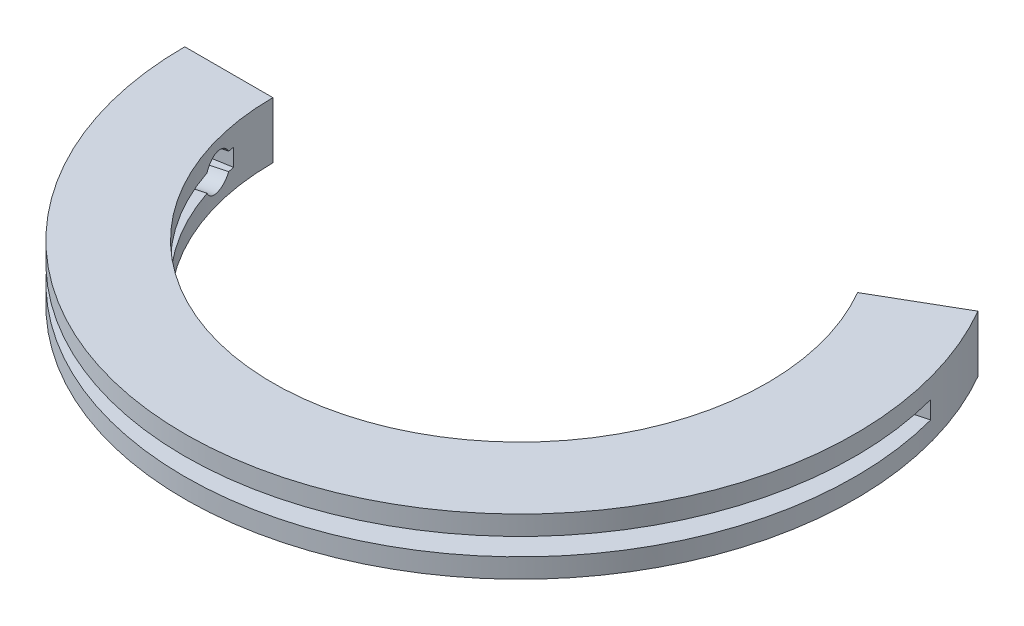
SolidWorks part; units mm, degrees
ref_plane "前视基准面" through (0, 0, 0) normal (0, 0, 1) x (1, 0, 0)
ref_plane "上视基准面" through (0, 0, 0) normal (0, 1, 0) x (1, 0, 0)
ref_plane "右视基准面" through (0, 0, 0) normal (1, 0, 0) x (0, 0, -1)
sketch "草图4" plane through (0, 0, 0) normal (0, 0, 1) x (1, 0, 0)
  line L1 (-949.5262, 0) -> (-949.5262, -80)
  line L2 (-949.5262, -80) -> (-700, -80)
  line L5 (-750, 436.001) -> (-750, -447.2545) construction
  line L6 (-700, 80) -> (-949.5262, 80)
  line L7 (-949.5262, 80) -> (-949.5262, 0)
  line L8 (0, 0) -> (0, 457.5891) construction
  line L9 (0, 50) -> (0, -50) construction
  line L10 (-700, 80) -> (-700, -80)
  line L11 (0, 533.1534) -> (0, -616.7503) construction
  line L12 (0, 0) -> (-1108.9843, 0) construction
  dimension "D1" = 750
  dimension "D2" = 700
  dimension "D3" = 80
  dimension "D4" = 950
  dimension "D5" = 160
revolve "旋转3" add sketch "草图4" angle 210 about L8
sketch "草图7" plane through (0, 0, 0) normal (0, 1, 0) x (1, 0, 0)
  line L0 (0, 0) -> (269.1765, -1004.5805) construction
  line L1 (-700, 0) -> (-949.5262, 0) construction
  line L2 (0, 0) -> (-1229.8518, -329.5378) construction
  dimension "D1" = 105
  dimension "D2" = 90
sketch "草图9" plane through (0, 0, 0) normal (0, 0, 1) x (1, 0, 0)
  line L0 (0, 442.4596) -> (0, -553.6878) construction
ref_plane "基准面5" through (0, 0, 0) normal (0.2588, 0, 0.9659) x (0.9659, 0, -0.2588)
sketch "草图10" plane through (0, 0, 0) normal (0.2588, 0, 0.9659) x (0.9659, 0, -0.2588)
  line L0 (-750, 50) -> (750, 50)
  line L5 (-1326.134, 0) -> (1077.1302, 0) construction
  line L6 (-800, 0) -> (800, 0)
  arc A0 (-750, 50) -> (-800, 0) centre (-750, 0) ccw
  arc A1 (800, 0) -> (750, 50) centre (750, 0) ccw
revolve "切除-旋转5" cut sketch "草图10" angle 360 about L5
sketch "草图11" plane through (0, 0, 0) normal (0.2588, 0, 0.9659) x (0.9659, 0, -0.2588)
  line L0 (-1123.767, 25) -> (-1123.767, -25)
  line L1 (0, 0) -> (-1273.2363, 0) construction
  line L2 (-1123.767, 25) -> (0, 25)
  line L3 (0, 442.4596) -> (0, -553.6878) construction
  line L4 (0, 25) -> (0, -25)
  line L5 (0, -25) -> (-1123.767, -25)
  dimension "D1" = 25
  dimension "D2" = 50
revolve "切除-旋转6" cut sketch "草图11" angle 5 about L4 other way angle 180
